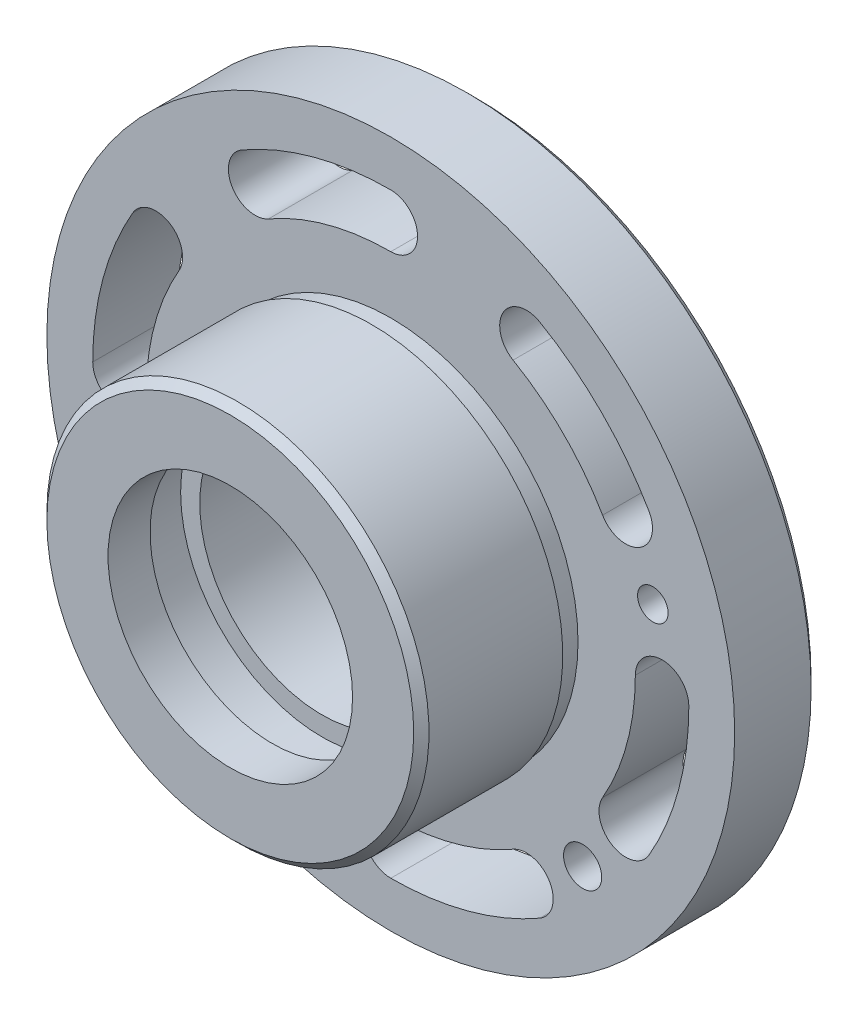
SolidWorks part; units mm, degrees
ref_plane "前视基准面" through (0, 0, 0) normal (0, 0, 1) x (1, 0, 0)
ref_plane "上视基准面" through (0, 0, 0) normal (0, 1, 0) x (1, 0, 0)
ref_plane "右视基准面" through (0, 0, 0) normal (1, 0, 0) x (0, 0, -1)
sketch "草图1" plane through (0, 0, 0) normal (0, 0, 1) x (1, 0, 0)
  circle A0 centre (0, 0) radius 90
  dimension "D1" = 180
extrude "凸台-拉伸1" add sketch "草图1" along normal blind 22
sketch "草图2" plane through (0, 0, 22) normal (0, 0, 1) x (1, 0, 0)
  circle A0 centre (0, 0) radius 50
  dimension "D1" = 100
extrude "凸台-拉伸2" add sketch "草图2" along normal blind 42
sketch "草图3" plane through (0, 0, 22) normal (0, 0, 1) x (1, 0, 0)
  circle A2 centre (0, 0) radius 49
  circle A3 centre (0, 0) radius 49
  dimension "D1" = 1
extrude "切除-拉伸1" cut sketch "草图3" along normal blind 5 flip side to cut
sketch "草图4" plane through (0, 0, 64) normal (0, 0, 1) x (1, 0, 0)
  circle A0 centre (0, 0) radius 32
  dimension "D1" = 64
extrude "切除-拉伸2" cut sketch "草图4" against normal through all
sketch "草图5" plane through (0, 0, 64) normal (0, 0, 1) x (1, 0, 0)
  circle A0 centre (0, 0) radius 37
  dimension "D1" = 74
extrude "切除-拉伸3" cut sketch "草图5" along normal blind 13 from offset 24 offset against normal yes
sketch "草图6" plane through (0, 0, 0) normal (0, 0, -1) x (-1, 0, 0)
  circle A0 centre (0, 0) radius 52
  dimension "D1" = 104
extrude "切除-拉伸4" cut sketch "草图6" against normal blind 6
chamfer "倒角1" distance 2 angle 45 3 edges at (50, 0, 64) (-32, 0, 6) (90, 0, 0)
sketch "草图7" plane through (0, 0, 22) normal (0, 0, 1) x (1, 0, 0)
  line L0 (0, 0) -> (0, 100.8335) construction
  circle A0 centre (0, 0) radius 71 construction
  arc A1 (0, 71) -> (-35.5, 61.4878) centre (0, 0) ccw construction
  arc A2 (0, 78) -> (-39, 67.55) centre (0, 0) ccw
  arc A3 (0, 64) -> (-32, 55.4256) centre (0, 0) ccw
  arc A4 (0, 64) -> (0, 78) centre (0, 71) ccw
  arc A5 (-39, 67.55) -> (-32, 55.4256) centre (-35.5, 61.4878) ccw
  point P6 (-18.3762, 68.5807)
  dimension "D1" = 142
  dimension "D2" = 7
extrude "切除-拉伸5" cut sketch "草图7" against normal through all
pattern_circular "阵列(圆周)1" count 6 over 360 about axis through (0, 0, 0) along (0, 0, 1) of "切除-拉伸5"
sketch "草图8" plane through (0, 0, 22) normal (0, 0, 1) x (1, 0, 0)
  line L0 (0, 0) -> (94.9333, 0) construction
  line L1 (0, 0) -> (0, -38.4719) construction
  line L2 (0, 0) -> (68.5807, 18.3762) construction
  line L3 (0, 0) -> (50.2046, -50.2046) construction
  circle A0 centre (0, 0) radius 71 construction
  point P0 (68.5807, 18.3762)
  point P1 (50.2046, -50.2046)
  dimension "D1" = 15
  dimension "D2" = 45
hole_wizard "Ø10.0mm 暗销孔2" positions "草图8" profile "草图10" hole size "Ø10.0" standard "GB"
sketch "草图10" plane through (50.2046, -50.2046, 22) normal (1, 0, 0) x (0, -1, 0)
  line L0 (0, 0) -> (0, 22)
  line L1 (0, 22) -> (5, 22)
  line L2 (5, 22) -> (5, 0)
  line L5 (5, 0) -> (0, 0)
  line L11 (0, -6.35) -> (0, 107.95) construction
  dimension "通孔孔直径" = 10
  dimension "通孔孔深度" = 22
sketch "草图11" plane through (0, 0, 22) normal (0, 0, 1) x (1, 0, 0)
  point P0 (68.5807, 18.3762)
hole_wizard "Ø8.0mm 暗销孔1" positions "草图11" profile "草图12" hole size "Ø8.0" standard "GB" end condition up to next
sketch "草图12" plane through (68.5807, 18.3762, 22) normal (1, 0, 0) x (0, -1, 0)
  line L0 (0, 0) -> (0, 22)
  line L1 (0, 22) -> (4, 22)
  line L2 (4, 22) -> (4, 0)
  line L5 (4, 0) -> (0, 0)
  line L11 (0, -6.35) -> (0, 107.95) construction
  dimension "通孔孔直径" = 8
  dimension "通孔孔深度" = 22
